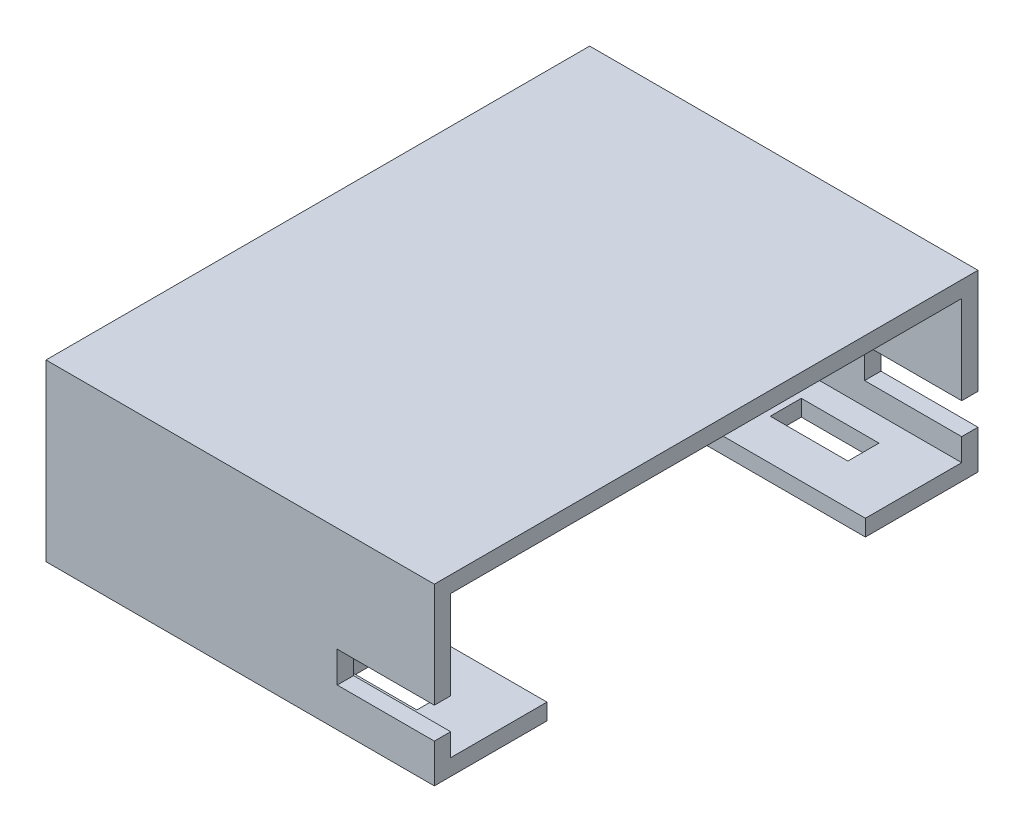
SolidWorks part; units mm, degrees
ref_plane "Alzado" through (0, 0, 0) normal (0, 0, 1) x (1, 0, 0)
ref_plane "Planta" through (0, 0, 0) normal (0, 1, 0) x (1, 0, 0)
ref_plane "Vista lateral" through (0, 0, 0) normal (1, 0, 0) x (0, 0, -1)
ref_plane "Plano4" through (0, -4.5, 0) normal (0, -1, 0) x (1, 0, 0)
sketch "Croquis1" plane through (0, -4.5, 0) normal (0, -1, 0) x (1, 0, 0)
  line L0 (0, -7) -> (10, -7)
  line L1 (10, -7) -> (10, 7)
  line L2 (10, 7) -> (0, 7)
  line L3 (0, 7) -> (0, -7)
extrude "Saliente-Extruir1" add sketch "Croquis1" against normal blind 4.5
sketch "Croquis2" plane through (10, 0, 0) normal (1, 0, 0) x (0, 0, -1)
  line L0 (4.1, -4.5) -> (4.1, -0.42)
  line L1 (4.1, -0.42) -> (-4.1, -0.42)
  line L2 (-4.1, -0.42) -> (-4.1, -4.5)
  line L3 (-4.1, -4.5) -> (4.1, -4.5)
extrude "Cortar-Extruir1" cut sketch "Croquis2" against normal blind 5
ref_plane "Plano5" through (0, 0, 6.58) normal (0, 0, 1) x (1, 0, 0)
sketch "Croquis3" plane through (0, 0, 6.58) normal (0, 0, 1) x (1, 0, 0)
  line L0 (10, -4.08) -> (10, -0.42)
  line L1 (10, -0.42) -> (5, -0.42)
  line L2 (5, -0.42) -> (5, -4.08)
  line L3 (5, -4.08) -> (10, -4.08)
extrude "Cortar-Extruir2" cut sketch "Croquis3" against normal up to next
ref_plane "Plano6" through (0, 0, -6.58) normal (0, 0, -1) x (-1, 0, 0)
sketch "Croquis4" plane through (0, 0, -6.58) normal (0, 0, -1) x (-1, 0, 0)
  line L0 (-10, -4.08) -> (-5, -4.08)
  line L1 (-5, -4.08) -> (-5, -0.42)
  line L2 (-5, -0.42) -> (-10, -0.42)
  line L3 (-10, -0.42) -> (-10, -4.08)
extrude "Cortar-Extruir3" cut sketch "Croquis4" against normal up to next
sketch "Croquis5" plane through (0, 0, -7) normal (0, 0, -1) x (-1, 0, 0)
  line L0 (-10, -3.5) -> (-7.5, -3.5)
  line L1 (-7.5, -3.5) -> (-7.5, -2.7)
  line L2 (-7.5, -2.7) -> (-10, -2.7)
  line L3 (-10, -2.7) -> (-10, -3.5)
extrude "Cortar-Extruir4" cut sketch "Croquis5" against normal up to next
sketch "Croquis6" plane through (0, 0, 7) normal (0, 0, 1) x (1, 0, 0)
  line L0 (10, -3.5) -> (10, -2.7)
  line L1 (10, -2.7) -> (7.5, -2.7)
  line L2 (7.5, -2.7) -> (7.5, -3.5)
  line L3 (7.5, -3.5) -> (10, -3.5)
extrude "Cortar-Extruir5" cut sketch "Croquis6" against normal through all
sketch "Croquis7" plane through (0, -4.5, 0) normal (0, -1, 0) x (1, 0, 0)
  line L0 (8.5, 5.95) -> (6.5, 5.95)
  line L1 (6.5, 5.95) -> (6.5, 5.15)
  line L2 (6.5, 5.15) -> (8.5, 5.15)
  line L3 (8.5, 5.15) -> (8.5, 5.95)
extrude "Cortar-Extruir6" cut sketch "Croquis7" against normal up to next
sketch "Croquis8" plane through (0, -4.5, 0) normal (0, -1, 0) x (1, 0, 0)
  line L0 (8.5, -5.15) -> (6.5, -5.15)
  line L1 (6.5, -5.15) -> (6.5, -5.95)
  line L2 (6.5, -5.95) -> (8.5, -5.95)
  line L3 (8.5, -5.95) -> (8.5, -5.15)
extrude "Cortar-Extruir7" cut sketch "Croquis8" against normal up to next
